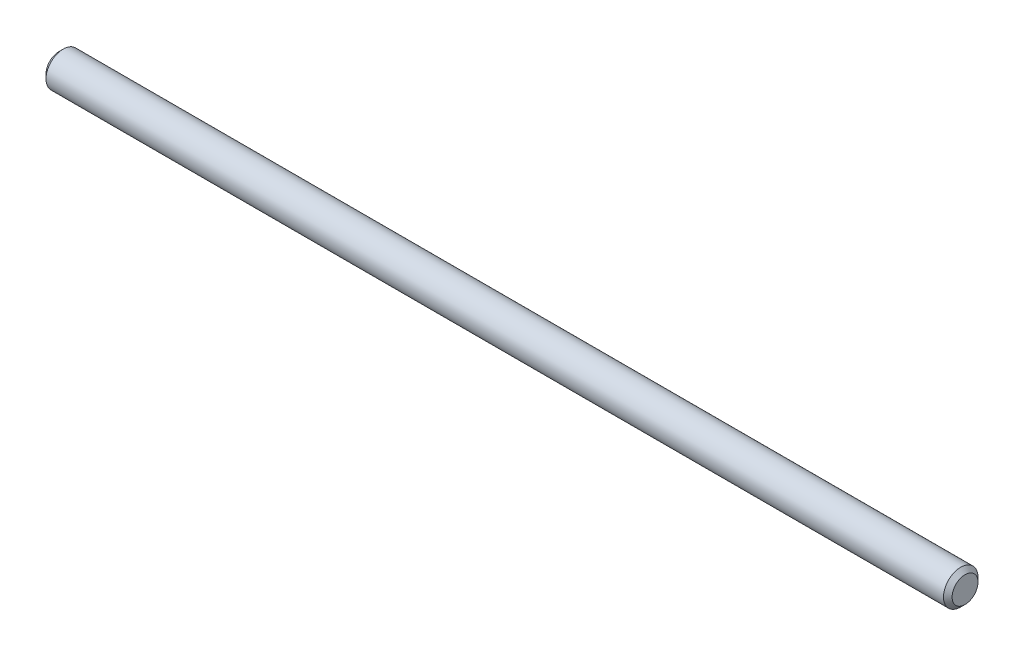
SolidWorks part; units mm, degrees
ref_plane "Front Plane" through (0, 0, 0) normal (0, 0, 1) x (1, 0, 0)
ref_plane "Top Plane" through (0, 0, 0) normal (0, 1, 0) x (1, 0, 0)
ref_plane "Right Plane" through (0, 0, 0) normal (1, 0, 0) x (0, 0, -1)
sketch "Sketch1" plane through (0, 0, 0) normal (1, 0, 0) x (0, 0, -1)
  circle A0 centre (0, 0) radius 2
  dimension "D1" = 4
extrude "Boss-Extrude1" add sketch "Sketch1" along normal mid plane 105
cosmetic thread "Cosmetic Thread1" parameters "D1"=8, "D2"=3.22
cosmetic thread "Cosmetic Thread3" parameters "D1"=8, "D2"=3.22
chamfer "Chamfer1" distance 0.5 angle 45 2 edges at (52.5, 0, -2) (-52.5, 0, -2)
